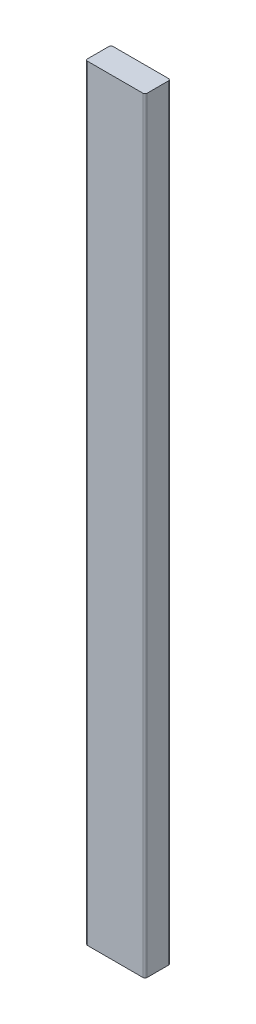
SolidWorks part; units mm, degrees
ref_plane "Front" through (0, 0, 0) normal (0, 0, 1) x (1, 0, 0)
ref_plane "Top" through (0, 0, 0) normal (0, 1, 0) x (1, 0, 0)
ref_plane "Right" through (0, 0, 0) normal (1, 0, 0) x (0, 0, -1)
sketch "Sketch1" plane through (0, 0, 0) normal (0, 1, 0) x (1, 0, 0)
  line L1 (44.45, 19.05) -> (-44.45, 19.05)
  line L2 (44.45, 19.05) -> (44.45, -19.05)
  line L3 (44.45, -19.05) -> (-44.45, -19.05)
  line L4 (-44.45, 19.05) -> (-44.45, -19.05)
  line L5 (44.45, 19.05) -> (-44.45, -19.05) construction
  line L6 (44.45, -19.05) -> (-44.45, 19.05) construction
  point P0 (0, 0)
  dimension "D1" = 38.1
  dimension "D2" = 88.9
extrude "Boss-Extrude1" add sketch "Sketch1" along normal blind 1143
hole_wizard "1/4 (0.25) Diameter Hole1" positions "Sketch3" profile "Sketch4" hole size "1/4" standard "ANSI Inch"
sketch "Sketch3" plane through (0, 0, -19.05) normal (0, 0, -1) x (-1, 0, 0)
  line L0 (-44.45, 0) -> (44.45, 0) construction
  point P0 (0, 52.3875)
  point P12 (0, 0)
  point P30 (0, 398.4625)
  point P31 (0, 744.5375)
  point P32 (0, 1090.6125)
  dimension "D1" = 52.3875
  dimension "D2" = 4
sketch "Sketch4" plane through (0, 52.3875, -19.05) normal (1, 0, 0) x (0, 1, 0)
  line L0 (0, 0) -> (0, 38.1)
  line L1 (0, 38.1) -> (3.175, 38.1)
  line L2 (3.175, 38.1) -> (3.175, 0)
  line L5 (3.175, 0) -> (0, 0)
  line L11 (0, -6.35) -> (0, 107.95) construction
  dimension "Thru Hole Dia." = 6.35
  dimension "Thru Hole Depth" = 38.1
fillet "Fillet1" radius 3.175 4 edges at (-44.45, 571.5, 19.05) (-44.45, 571.5, -19.05) (44.45, 571.5, 19.05) (44.45, 571.5, -19.05)
